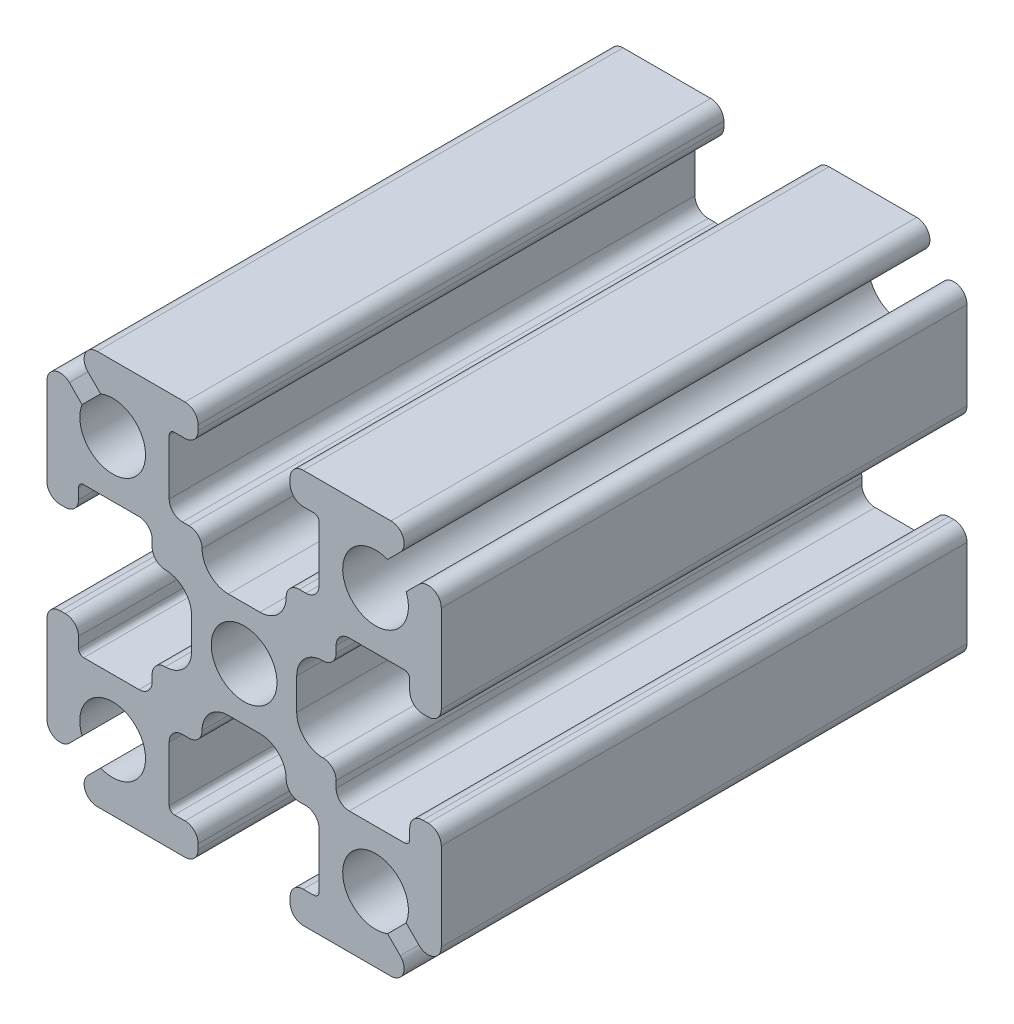
SolidWorks part; units mm, degrees
ref_plane "Front" through (0, 0, 0) normal (0, 0, 1) x (1, 0, 0)
ref_plane "Top" through (0, 0, 0) normal (0, 1, 0) x (1, 0, 0)
ref_plane "Right" through (0, 0, 0) normal (1, 0, 0) x (0, 0, -1)
sketch "Sketch1" plane through (0, 0, 0) normal (0, 0, 1) x (1, 0, 0)
  line L0 (6.6464, 5.9393) -> (6.1636, 5.4565)
  line L1 (5.4565, 6.1636) -> (5.9393, 6.6464)
  line L2 (5.5858, 7.5) -> (2.25, 7.5)
  line L3 (1.75, 7) -> (1.75, 6.8)
  line L4 (2.25, 6.3) -> (2.65, 6.3)
  line L5 (2.85, 6.1) -> (2.85, 4)
  line L6 (2.35, 3.5) -> (2.1, 3.5)
  line L7 (0.6, 2) -> (-0.6, 2)
  line L8 (-2.1, 3.5) -> (-2.35, 3.5)
  line L9 (-2.85, 4) -> (-2.85, 6.1)
  line L10 (-2.65, 6.3) -> (-2.25, 6.3)
  line L11 (-1.75, 6.8) -> (-1.75, 7)
  line L12 (-2.25, 7.5) -> (-5.5858, 7.5)
  line L13 (-5.9393, 6.6464) -> (-5.4565, 6.1636)
  line L14 (-6.1636, 5.4565) -> (-6.6464, 5.9393)
  line L15 (-7.5, 5.5858) -> (-7.5, 2.25)
  line L16 (-7, 1.75) -> (-6.8, 1.75)
  line L17 (-6.3, 2.25) -> (-6.3, 2.65)
  line L18 (-6.1, 2.85) -> (-4, 2.85)
  line L19 (-3.5, 2.35) -> (-3.5, 2.1)
  line L20 (-2, 0.6) -> (-2, -0.6)
  line L21 (-3.5, -2.1) -> (-3.5, -2.35)
  line L22 (-4, -2.85) -> (-6.1, -2.85)
  line L23 (-6.3, -2.65) -> (-6.3, -2.25)
  line L24 (-6.8, -1.75) -> (-7, -1.75)
  line L25 (-7.5, -2.25) -> (-7.5, -5.5858)
  line L26 (-6.6464, -5.9393) -> (-6.1636, -5.4565)
  line L27 (-5.4565, -6.1636) -> (-5.9393, -6.6464)
  line L28 (-5.5858, -7.5) -> (-2.25, -7.5)
  line L29 (-1.75, -7) -> (-1.75, -6.8)
  line L30 (-2.25, -6.3) -> (-2.65, -6.3)
  line L31 (-2.85, -6.1) -> (-2.85, -4)
  line L32 (-2.35, -3.5) -> (-2.1, -3.5)
  line L33 (-0.6, -2) -> (0.6, -2)
  line L34 (2.1, -3.5) -> (2.35, -3.5)
  line L35 (2.85, -4) -> (2.85, -6.1)
  line L36 (2.65, -6.3) -> (2.25, -6.3)
  line L37 (1.75, -6.8) -> (1.75, -7)
  line L38 (2.25, -7.5) -> (5.5858, -7.5)
  line L39 (5.9393, -6.6464) -> (5.4565, -6.1636)
  line L40 (6.1636, -5.4565) -> (6.6464, -5.9393)
  line L41 (7.5, -5.5858) -> (7.5, -2.25)
  line L42 (7, -1.75) -> (6.8, -1.75)
  line L43 (6.3, -2.25) -> (6.3, -2.65)
  line L44 (6.1, -2.85) -> (4, -2.85)
  line L45 (3.5, -2.35) -> (3.5, -2.1)
  line L46 (2, -0.6) -> (2, 0.6)
  line L47 (3.5, 2.1) -> (3.5, 2.35)
  line L48 (4, 2.85) -> (6.1, 2.85)
  line L49 (6.3, 2.65) -> (6.3, 2.25)
  line L50 (6.8, 1.75) -> (7, 1.75)
  line L51 (7.5, 2.25) -> (7.5, 5.5858)
  circle A0 centre (0, 0) radius 1.25
  arc A1 (6.1636, 5.4565) -> (5.4565, 6.1636) centre (5, 5) cw
  arc A2 (5.9393, 6.6464) -> (5.5858, 7.5) centre (5.5858, 7) ccw
  arc A3 (2.25, 7.5) -> (1.75, 7) centre (2.25, 7) ccw
  arc A4 (1.75, 6.8) -> (2.25, 6.3) centre (2.25, 6.8) ccw
  arc A5 (2.65, 6.3) -> (2.85, 6.1) centre (2.65, 6.1) cw
  arc A6 (2.85, 4) -> (2.35, 3.5) centre (2.35, 4) cw
  arc A7 (2.1, 3.5) -> (1.6, 3) centre (2.1, 3) ccw
  arc A8 (1.6, 3) -> (0.6, 2) centre (0.6, 3) cw
  arc A9 (-0.6, 2) -> (-1.6, 3) centre (-0.6, 3) cw
  arc A10 (-1.6, 3) -> (-2.1, 3.5) centre (-2.1, 3) ccw
  arc A11 (-2.35, 3.5) -> (-2.85, 4) centre (-2.35, 4) cw
  arc A12 (-2.85, 6.1) -> (-2.65, 6.3) centre (-2.65, 6.1) cw
  arc A13 (-2.25, 6.3) -> (-1.75, 6.8) centre (-2.25, 6.8) ccw
  arc A14 (-1.75, 7) -> (-2.25, 7.5) centre (-2.25, 7) ccw
  arc A15 (-5.5858, 7.5) -> (-5.9393, 6.6464) centre (-5.5858, 7) ccw
  arc A16 (-5.4565, 6.1636) -> (-6.1636, 5.4565) centre (-5, 5) cw
  arc A17 (-6.6464, 5.9393) -> (-7.5, 5.5858) centre (-7, 5.5858) ccw
  arc A18 (-7.5, 2.25) -> (-7, 1.75) centre (-7, 2.25) ccw
  arc A19 (-6.8, 1.75) -> (-6.3, 2.25) centre (-6.8, 2.25) ccw
  arc A20 (-6.3, 2.65) -> (-6.1, 2.85) centre (-6.1, 2.65) cw
  arc A21 (-4, 2.85) -> (-3.5, 2.35) centre (-4, 2.35) cw
  arc A22 (-3.5, 2.1) -> (-3, 1.6) centre (-3, 2.1) ccw
  arc A23 (-3, 1.6) -> (-2, 0.6) centre (-3, 0.6) cw
  arc A24 (-2, -0.6) -> (-3, -1.6) centre (-3, -0.6) cw
  arc A25 (-3, -1.6) -> (-3.5, -2.1) centre (-3, -2.1) ccw
  arc A26 (-3.5, -2.35) -> (-4, -2.85) centre (-4, -2.35) cw
  arc A27 (-6.1, -2.85) -> (-6.3, -2.65) centre (-6.1, -2.65) cw
  arc A28 (-6.3, -2.25) -> (-6.8, -1.75) centre (-6.8, -2.25) ccw
  arc A29 (-7, -1.75) -> (-7.5, -2.25) centre (-7, -2.25) ccw
  arc A30 (-7.5, -5.5858) -> (-6.6464, -5.9393) centre (-7, -5.5858) ccw
  arc A31 (-6.1636, -5.4565) -> (-5.4565, -6.1636) centre (-5, -5) cw
  arc A32 (-5.9393, -6.6464) -> (-5.5858, -7.5) centre (-5.5858, -7) ccw
  arc A33 (-2.25, -7.5) -> (-1.75, -7) centre (-2.25, -7) ccw
  arc A34 (-1.75, -6.8) -> (-2.25, -6.3) centre (-2.25, -6.8) ccw
  arc A35 (-2.65, -6.3) -> (-2.85, -6.1) centre (-2.65, -6.1) cw
  arc A36 (-2.85, -4) -> (-2.35, -3.5) centre (-2.35, -4) cw
  arc A37 (-2.1, -3.5) -> (-1.6, -3) centre (-2.1, -3) ccw
  arc A38 (-1.6, -3) -> (-0.6, -2) centre (-0.6, -3) cw
  arc A39 (0.6, -2) -> (1.6, -3) centre (0.6, -3) cw
  arc A40 (1.6, -3) -> (2.1, -3.5) centre (2.1, -3) ccw
  arc A41 (2.35, -3.5) -> (2.85, -4) centre (2.35, -4) cw
  arc A42 (2.85, -6.1) -> (2.65, -6.3) centre (2.65, -6.1) cw
  arc A43 (2.25, -6.3) -> (1.75, -6.8) centre (2.25, -6.8) ccw
  arc A44 (1.75, -7) -> (2.25, -7.5) centre (2.25, -7) ccw
  arc A45 (5.5858, -7.5) -> (5.9393, -6.6464) centre (5.5858, -7) ccw
  arc A46 (5.4565, -6.1636) -> (6.1636, -5.4565) centre (5, -5) cw
  arc A47 (6.6464, -5.9393) -> (7.5, -5.5858) centre (7, -5.5858) ccw
  arc A48 (7.5, -2.25) -> (7, -1.75) centre (7, -2.25) ccw
  arc A49 (6.8, -1.75) -> (6.3, -2.25) centre (6.8, -2.25) ccw
  arc A50 (6.3, -2.65) -> (6.1, -2.85) centre (6.1, -2.65) cw
  arc A51 (4, -2.85) -> (3.5, -2.35) centre (4, -2.35) cw
  arc A52 (3.5, -2.1) -> (3, -1.6) centre (3, -2.1) ccw
  arc A53 (3, -1.6) -> (2, -0.6) centre (3, -0.6) cw
  arc A54 (2, 0.6) -> (3, 1.6) centre (3, 0.6) cw
  arc A55 (3, 1.6) -> (3.5, 2.1) centre (3, 2.1) ccw
  arc A56 (3.5, 2.35) -> (4, 2.85) centre (4, 2.35) cw
  arc A57 (6.1, 2.85) -> (6.3, 2.65) centre (6.1, 2.65) cw
  arc A58 (6.3, 2.25) -> (6.8, 1.75) centre (6.8, 2.25) ccw
  arc A59 (7, 1.75) -> (7.5, 2.25) centre (7, 2.25) ccw
  arc A60 (7.5, 5.5858) -> (6.6464, 5.9393) centre (7, 5.5858) ccw
extrude "Boss-Extrude1" add sketch "Sketch1" along normal blind 20
